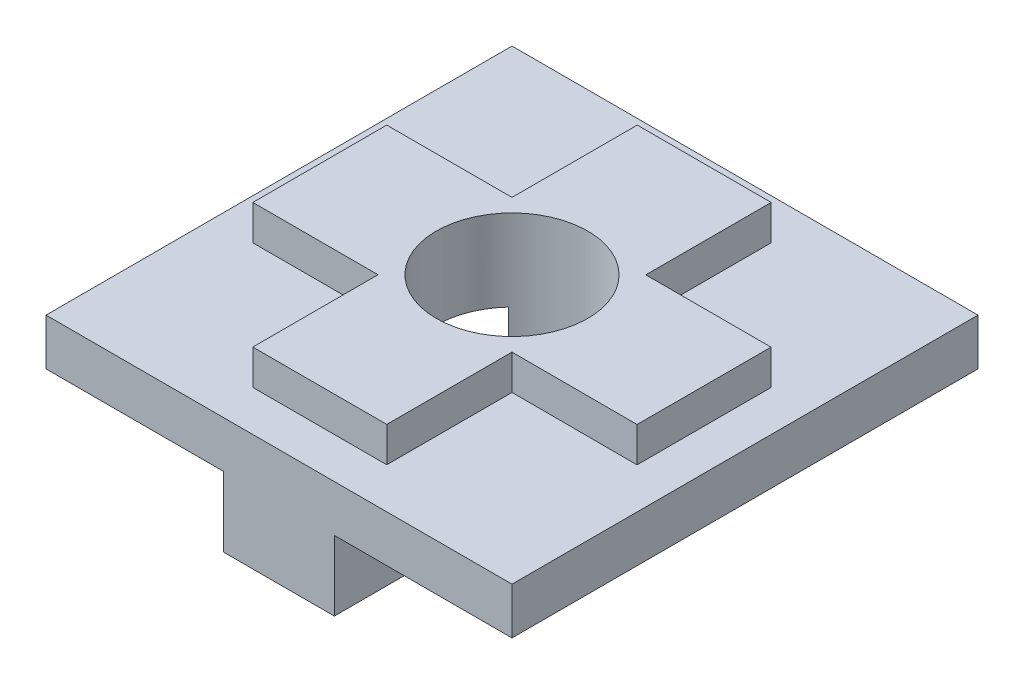
SolidWorks part; units mm, degrees
ref_plane "Front Plane" through (0, 0, 0) normal (0, 0, 1) x (1, 0, 0)
ref_plane "Top Plane" through (0, 0, 0) normal (0, 1, 0) x (1, 0, 0)
ref_plane "Right Plane" through (0, 0, 0) normal (1, 0, 0) x (0, 0, -1)
sketch "Sketch1" plane through (0, 0, 0) normal (0, 1, 0) x (1, 0, 0)
  line L1 (-10, 10) -> (10, 10)
  line L2 (-10, 10) -> (-10, -10)
  line L3 (-10, -10) -> (10, -10)
  line L4 (10, 10) -> (10, -10)
  line L5 (-10, 10) -> (10, -10) construction
  line L6 (-10, -10) -> (10, 10) construction
  point P0 (0, 0)
extrude "Boss-Extrude1" add sketch "Sketch1" along normal blind 2
sketch "Sketch3" plane through (0, 2, 0) normal (0, 1, 0) x (1, 0, 0)
  line L0 (-2.875, 8.25) -> (2.875, 8.25)
  line L1 (0, -55) -> (0, 55) construction
  line L2 (8.25, -2.8825) -> (8.25, 2.8675)
  line L3 (-2.875, 8.25) -> (-2.875, 2.875)
  line L4 (-2.875, -8.25) -> (2.875, -8.25)
  line L5 (-8.25, -2.875) -> (-8.25, 2.875)
  line L6 (-2.875, 2.875) -> (-8.25, 2.875)
  line L7 (-55, 0) -> (55, 0) construction
  line L8 (-8.25, -2.875) -> (-2.875, -2.875)
  line L9 (-2.875, -2.875) -> (-2.875, -8.25)
  line L10 (2.875, -8.25) -> (2.875, -2.875)
  line L11 (2.875, -2.875) -> (8.25, -2.8825)
  line L12 (8.25, 2.8675) -> (2.875, 2.8675)
  line L13 (2.875, 2.8675) -> (2.875, 8.25)
  point P2 (0, 8.25)
  point P8 (8.25, -0.0075)
  point P11 (0, -8.25)
  point P14 (-8.25, 0)
extrude "Boss-Extrude3" add sketch "Sketch3" along normal blind 1.5
sketch "Sketch6" plane through (0, 0, 0) normal (0, -1, 0) x (1, 0, 0)
  line L5 (10, -10) -> (-10, -10) construction
  line L6 (-2.375, 10) -> (2.375, 10)
  line L7 (-2.375, 10) -> (-2.375, -10)
  line L8 (-2.375, -10) -> (2.375, -10)
  line L9 (2.375, 10) -> (2.375, -10)
  line L10 (-2.375, 10) -> (2.375, -10) construction
  line L11 (-2.375, -10) -> (2.375, 10) construction
  point P0 (0, 0)
  dimension "D1" = 4.75
extrude "Boss-Extrude4" add sketch "Sketch6" along normal blind 3
hole_wizard "Tap Drill for M2.2 Helicoil1" positions "3DSketch1" profile "Sketch5" hole size "M2.2x0.45" standard "ANSI Metric" end condition through all
sketch3d "3DSketch1"
  point P0 (0, 3.5, 0)
sketch "Sketch5" plane through (0, 3.5, 0) normal (1, 0, 0) x (0, 0, 1)
  line L0 (0, 0) -> (0, 6.5)
  line L1 (0, 6.5) -> (3.25, 6.5)
  line L2 (3.25, 6.5) -> (3.25, 0)
  line L5 (3.25, 0) -> (0, 0)
  line L11 (0, -6.35) -> (0, 107.95) construction
  dimension "Thru Hole Dia." = 6.5
  dimension "Thru Hole Depth" = 6.5
